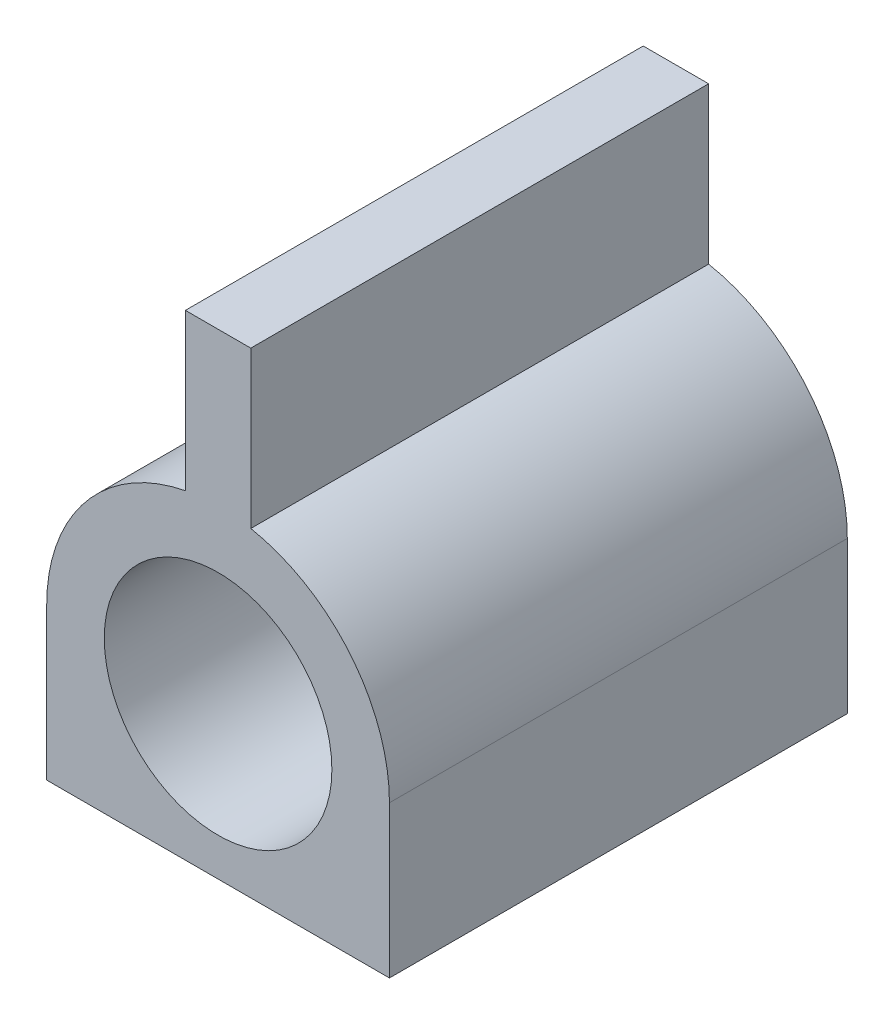
SolidWorks part; units mm, degrees
ref_plane "Front Plane" through (0, 0, 0) normal (0, 0, 1) x (1, 0, 0)
ref_plane "Top Plane" through (0, 0, 0) normal (0, 1, 0) x (1, 0, 0)
ref_plane "Right Plane" through (0, 0, 0) normal (1, 0, 0) x (0, 0, -1)
sketch "Sketch1" plane through (0, 0, 0) normal (0, 0, 1) x (1, 0, 0)
  line L0 (16.637, -14.732) -> (-16.637, -14.732)
  line L1 (-16.637, -14.732) -> (-16.637, 0)
  line L2 (16.637, 0) -> (16.637, -14.732)
  line L3 (-3.175, 16.3312) -> (-3.175, 31.496)
  line L4 (-3.175, 31.496) -> (3.175, 31.496)
  line L5 (3.175, 31.496) -> (3.175, 16.3312)
  line L6 (0, 31.496) -> (0, -14.732) construction
  arc A0 (-16.637, 0) -> (-3.175, 16.3312) centre (0, 0) cw
  circle A1 centre (0, 0) radius 11.049
  arc A2 (3.175, 16.3312) -> (16.637, 0) centre (0, 0) cw
  dimension "D1" = 22.098
  dimension "D2" = 33.274
  dimension "D3" = 46.228
  dimension "D4" = 14.732
  dimension "D5" = 6.35
extrude "Boss-Extrude1" add sketch "Sketch1" along normal mid plane 44.45
